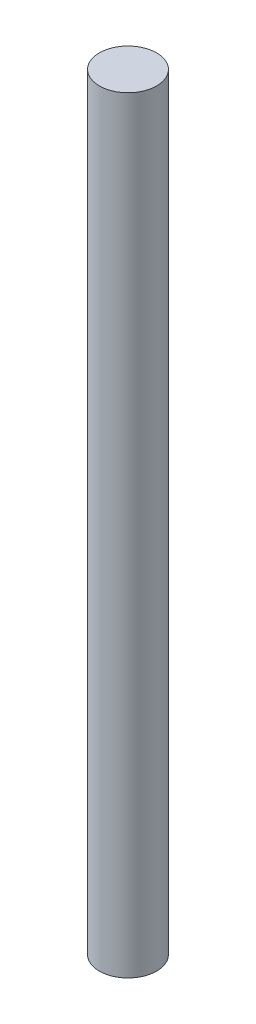
SolidWorks part; units mm, degrees
ref_plane "Front Plane" through (0, 0, 0) normal (0, 0, 1) x (1, 0, 0)
ref_plane "Top Plane" through (0, 0, 0) normal (0, 1, 0) x (1, 0, 0)
ref_plane "Right Plane" through (0, 0, 0) normal (1, 0, 0) x (0, 0, -1)
sketch "Sketch1" plane through (0, 0, 0) normal (0, 1, 0) x (1, 0, 0)
  circle A0 centre (0, 0) radius 6.35
  dimension "D1" = 12.7
extrude "Boss-Extrude1" add sketch "Sketch1" along normal mid plane 170
